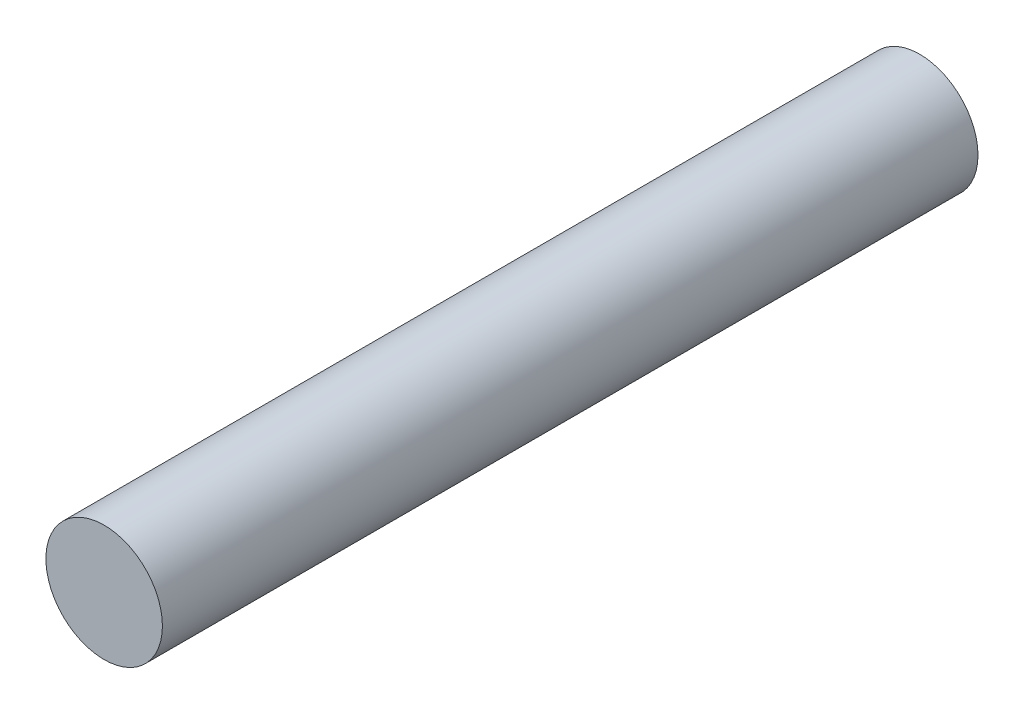
SolidWorks part; units mm, degrees
ref_plane "Спереди" through (0, 0, 0) normal (0, 0, 1) x (1, 0, 0)
ref_plane "Сверху" through (0, 0, 0) normal (0, 1, 0) x (1, 0, 0)
ref_plane "Справа" through (0, 0, 0) normal (1, 0, 0) x (0, 0, -1)
sketch "Эскиз1" plane through (0, 0, 0) normal (0, 0, 1) x (1, 0, 0)
  circle A0 centre (0, 0) radius 1
  dimension "D1" = 2
extrude "Бобышка-Вытянуть1" add sketch "Эскиз1" along normal blind 14
